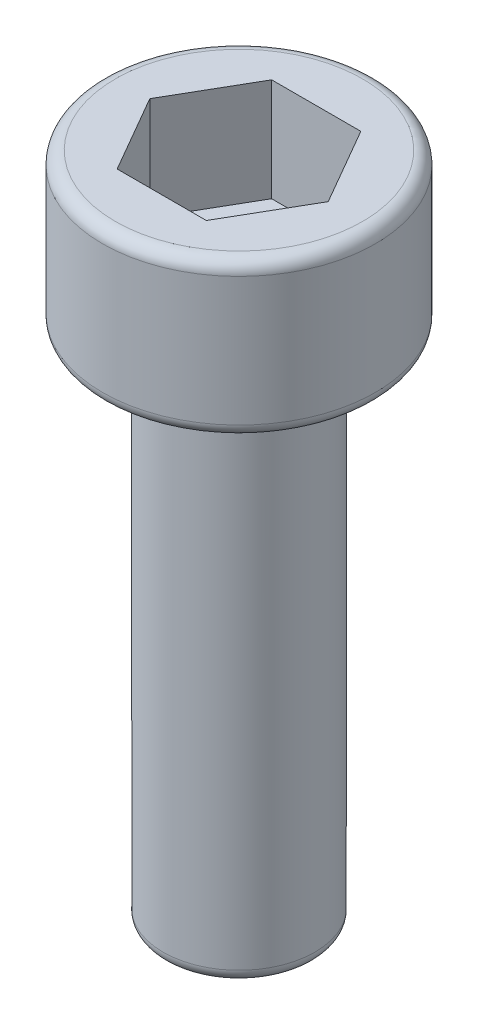
SolidWorks part; units mm, degrees
ref_plane "Front Plane" through (0, 0, 0) normal (0, 0, 1) x (1, 0, 0)
ref_plane "Top Plane" through (0, 0, 0) normal (0, 1, 0) x (1, 0, 0)
ref_plane "Right Plane" through (0, 0, 0) normal (1, 0, 0) x (0, 0, -1)
sketch "Sketch1" plane through (0, 0, 0) normal (0, 1, 0) x (1, 0, 0)
  circle A0 centre (0, 0) radius 2.65
  point P3 (0, 0)
  dimension "D1" = 5.3
extrude "Boss-Extrude1" add sketch "Sketch1" along normal blind 3
sketch "Sketch2" plane through (0, 0, 0) normal (0, -1, 0) x (1, 0, 0)
  circle A0 centre (0, 0) radius 1.475
  dimension "D1" = 2.95
extrude "Boss-Extrude2" add sketch "Sketch2" along normal blind 10
fillet "Fillet1" radius 0.25 3 edges at (0, -10, -1.475) (0, 3, 2.65) (0, 0, 2.65)
sketch "Sketch3" plane through (0, 3, 0) normal (0, 1, 0) x (1, 0, 0)
  line L0 (0, 0) -> (0, 2.4) construction
  line L1 (1.7321, 0) -> (0.866, 1.5)
  line L2 (0.866, 1.5) -> (-0.866, 1.5)
  line L3 (-0.866, 1.5) -> (-1.7321, 0)
  line L4 (-1.7321, 0) -> (-0.866, -1.5)
  line L5 (-0.866, -1.5) -> (0.866, -1.5)
  line L6 (0.866, -1.5) -> (1.7321, 0)
  circle A0 centre (0, 0) radius 1.5 construction
  circle A1 centre (0, 0) radius 2.4 construction
  dimension "D1" = 3
extrude "Cut-Extrude1" cut sketch "Sketch3" against normal blind 2
